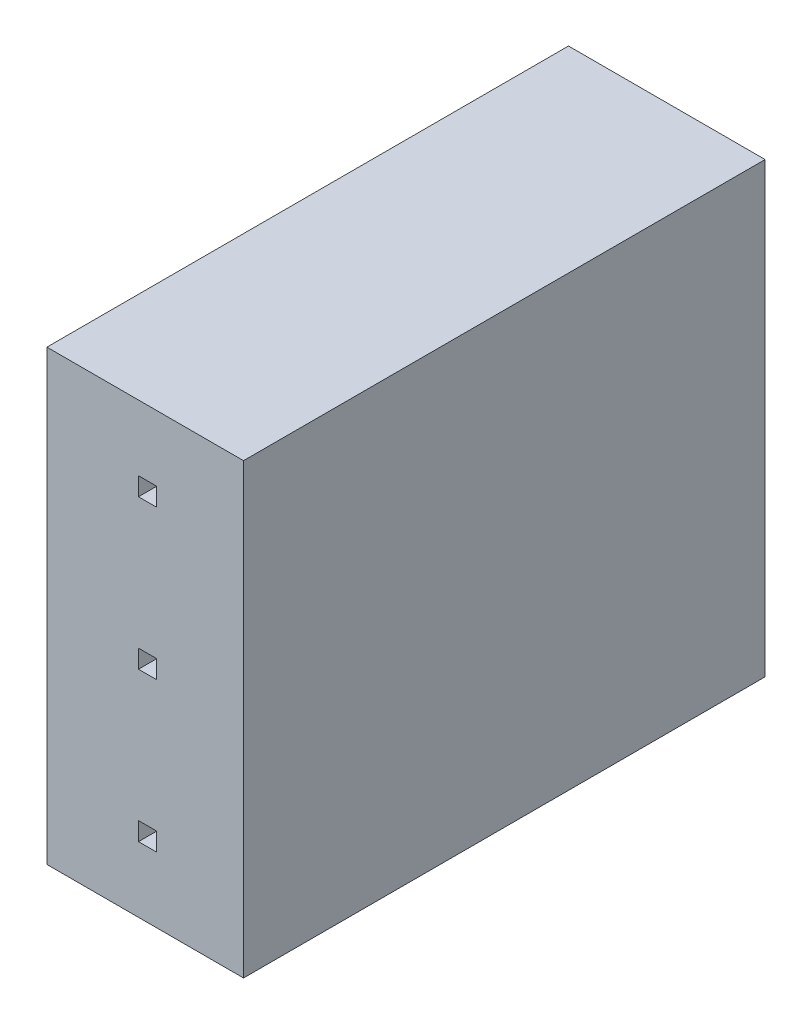
SolidWorks part; units mm, degrees
ref_plane "Front Plane" through (0, 0, 0) normal (0, 0, 1) x (1, 0, 0)
ref_plane "Top Plane" through (0, 0, 0) normal (0, 1, 0) x (1, 0, 0)
ref_plane "Right Plane" through (0, 0, 0) normal (1, 0, 0) x (0, 0, -1)
sketch "Sketch2" plane through (0, 0, 0) normal (0, 0, 1) x (-1, 0, 0)
  line L0 (-0.175, -3.0383) -> (0.175, -3.0383)
  line L1 (0.175, -3.0383) -> (0.175, -2.6883)
  line L2 (0.175, -2.6883) -> (-0.175, -2.6883)
  line L3 (-0.175, -2.6883) -> (-0.175, -3.0383)
  line L4 (0.175, 0.175) -> (-0.175, 0.175)
  line L5 (-0.175, 0.175) -> (-0.175, -0.175)
  line L6 (-0.175, -0.175) -> (0.175, -0.175)
  line L7 (0.175, -0.175) -> (0.175, 0.175)
  line L8 (1.9309, -4.295) -> (1.9309, 4.295)
  line L9 (1.9309, 4.295) -> (-1.8391, 4.295)
  line L10 (-1.8391, 4.295) -> (-1.8391, -4.295)
  line L11 (-1.8391, -4.295) -> (1.9309, -4.295)
  line L12 (0.175, 3.0383) -> (-0.175, 3.0383)
  line L13 (-0.175, 3.0383) -> (-0.175, 2.6883)
  line L14 (-0.175, 2.6883) -> (0.175, 2.6883)
  line L15 (0.175, 2.6883) -> (0.175, 3.0383)
  line L16 (0.125, 2.9883) -> (-0.125, 2.9883)
  line L17 (-0.125, 2.9883) -> (-0.125, 2.7383)
  line L18 (-0.125, 2.7383) -> (0.125, 2.7383)
  line L19 (0.125, 2.7383) -> (0.125, 2.9883)
  line L20 (2.0309, -4.395) -> (2.0309, 4.395) construction
  line L21 (2.0309, 4.395) -> (-1.9391, 4.395) construction
  line L22 (-1.9391, 4.395) -> (-1.9391, -4.395) construction
  line L23 (-1.9391, -4.395) -> (2.0309, -4.395) construction
  line L24 (0.125, 0.125) -> (-0.125, 0.125)
  line L25 (-0.125, 0.125) -> (-0.125, -0.125)
  line L26 (-0.125, -0.125) -> (0.125, -0.125)
  line L27 (0.125, -0.125) -> (0.125, 0.125)
  line L28 (0, 0) -> (1.9309, 0) construction
  line L29 (1.9309, 0) -> (2.0309, 0) construction
  line L31 (1.9309, 3) -> (2.0309, 3)
  line L32 (-0.125, -2.9883) -> (0.125, -2.9883)
  line L33 (0.125, -2.9883) -> (0.125, -2.7383)
  line L34 (0.125, -2.7383) -> (-0.125, -2.7383)
  line L35 (-0.125, -2.7383) -> (-0.125, -2.9883)
  line L37 (2.0309, 1) -> (1.9309, 1) construction
  point P10 (0, 0)
  point P37 (0, 0)
  dimension "D2" = 0.25
  dimension "D1" = 0.05
  dimension "D3" = 0.1
extrude "Boss-Extrude1" add sketch "Sketch2" along normal blind 10 contours L2 L3 L0 L1 L35 L34 L33 L32 | L34 L35 L32 L33 | L6 L7 L4 L5 L27 L26 L25 L24 | L26 L27 L24 L25 | L8 L9 L10 L11 | L13 L14 L15 L12
